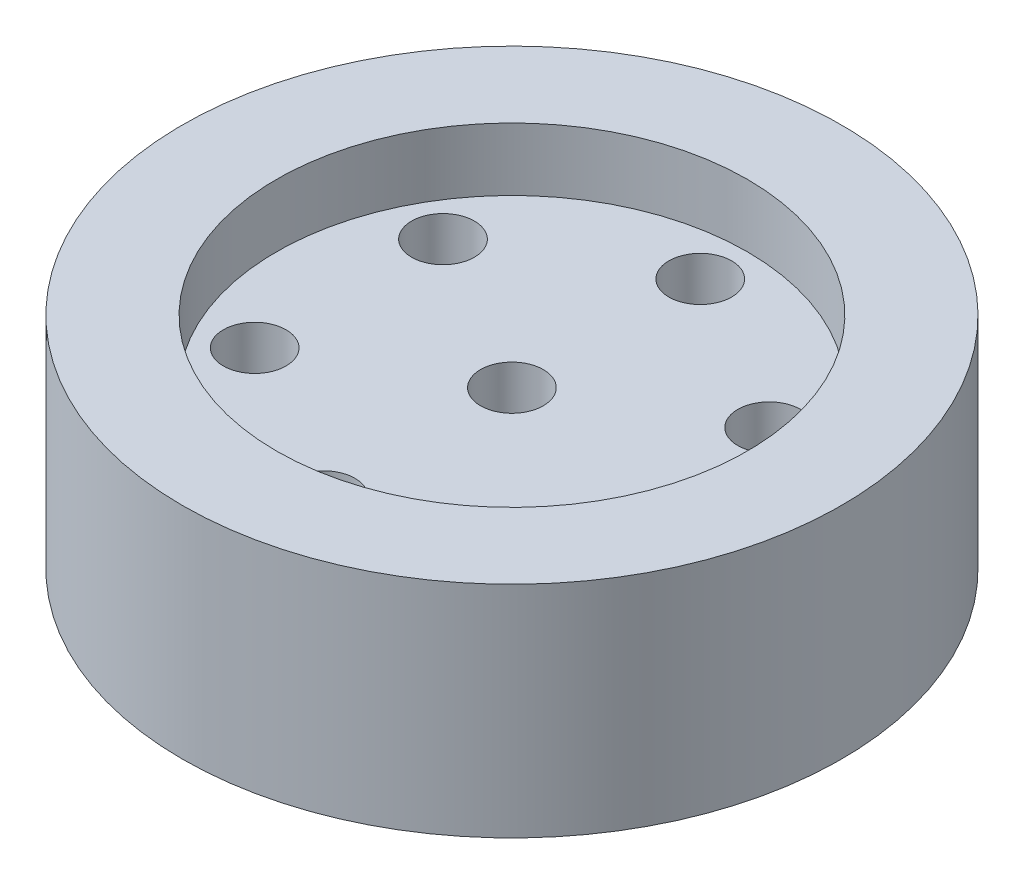
SolidWorks part; units mm, degrees
material "AISI 1035 Steel (SS)"
ref_plane "Front Plane" through (0, 0, 0) normal (0, 0, 1) x (1, 0, 0)
ref_plane "Top Plane" through (0, 0, 0) normal (0, 1, 0) x (1, 0, 0)
ref_plane "Right Plane" through (0, 0, 0) normal (1, 0, 0) x (0, 0, -1)
sketch "Sketch1" plane through (0, 0, 0) normal (0, 1, 0) x (1, 0, 0)
  circle A0 centre (0, 0) radius 21
  dimension "D1" = 42
extrude "Boss-Extrude1" add sketch "Sketch1" along normal mid plane 14
sketch "Sketch2" plane through (0, 7, 0) normal (0, 1, 0) x (1, 0, 0)
  circle A0 centre (0, 0) radius 15
extrude "Cut-Extrude1" cut sketch "Sketch2" against normal blind 4
sketch "Sketch3" plane through (0, -7, 0) normal (0, -1, 0) x (1, 0, 0)
  circle A0 centre (0, 0) radius 19
  circle A1 centre (0, 0) radius 5
  point P4 (0, 0)
  dimension "D1" = 38
  dimension "D2" = 10
extrude "Cut-Extrude2" cut sketch "Sketch3" against normal blind 4
sketch "Sketch4" plane through (0, -7, 0) normal (0, -1, 0) x (1, 0, 0)
  circle A0 centre (0, 0) radius 2
extrude "Cut-Extrude3" cut sketch "Sketch4" against normal through all
sketch "Sketch5" plane through (0, -3, 0) normal (0, -1, 0) x (1, 0, 0)
  circle A0 centre (0, 0) radius 12 construction
  circle A1 centre (0, 12) radius 2
  circle A2 centre (0, 0) radius 12 construction
  circle A3 centre (10.3923, 6) radius 2
  circle A4 centre (0, 0) radius 12 construction
  circle A5 centre (10.3923, -6) radius 2
  circle A6 centre (0, 0) radius 12 construction
  circle A7 centre (0, -12) radius 2
  circle A8 centre (0, 0) radius 12 construction
  circle A9 centre (-10.3923, -6) radius 2
  circle A10 centre (0, 0) radius 12 construction
  circle A11 centre (-10.3923, 6) radius 2
  point P22 (0, 0)
  dimension "D1" = 4
  dimension "D2" = 6
extrude "Cut-Extrude4" cut sketch "Sketch5" along normal blind 7 and the other way blind 29
